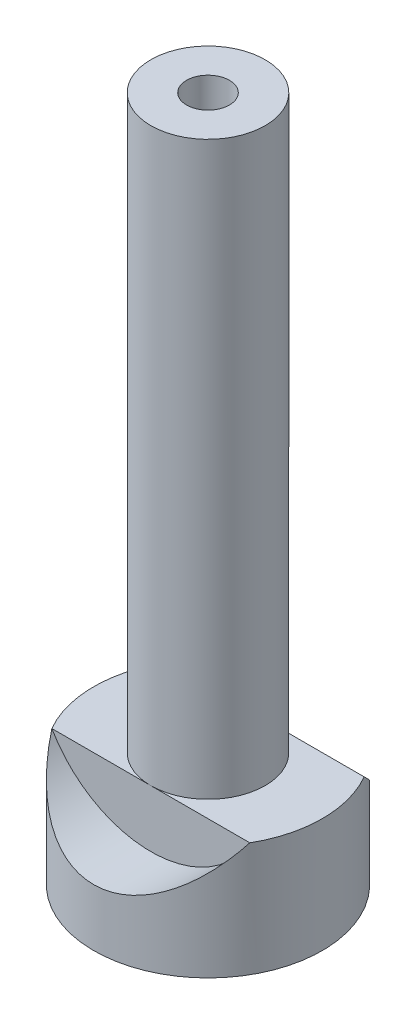
SolidWorks part; units mm, degrees
ref_plane "Front Plane" through (0, 0, 0) normal (0, 0, 1) x (1, 0, 0)
ref_plane "Top Plane" through (0, 0, 0) normal (0, 1, 0) x (1, 0, 0)
ref_plane "Right Plane" through (0, 0, 0) normal (1, 0, 0) x (0, 0, -1)
sketch "Sketch1" plane through (0, 0, 0) normal (0, 1, 0) x (1, 0, 0)
  circle A0 centre (0, 0) radius 6.35
  dimension "D1" = 12.7
extrude "Boss-Extrude1" add sketch "Sketch1" along normal blind 63.5
sketch "Sketch5" plane through (0, 0, 0) normal (0, -1, 0) x (1, 0, 0)
  circle A0 centre (0, 0) radius 12.7
  dimension "D1" = 25.4
extrude "Boss-Extrude2" add sketch "Sketch5" along normal blind 12.7
sketch "Sketch7" plane through (0, 0, 0) normal (0, 1, 0) x (1, 0, 0)
  circle A0 centre (0, 0) radius 8.89
  circle A1 centre (0, 0) radius 6.35
  dimension "D1" = 17.78
ref_plane "Plane1" through (0, 0, 6.35) normal (0, 0, 1) x (1, 0, 0)
sketch "Sketch10" plane through (0, 0, 6.35) normal (0, 0, 1) x (1, 0, 0)
  line L1 (12.7, 0) -> (-12.7, 0) construction
  circle A0 centre (0, 6.35) radius 12.7
  dimension "D1" = 25.4
  dimension "D2" = 6.35
extrude "Cut-Extrude5" cut sketch "Sketch10" along normal through all
ref_plane "Plane2" through (0, 0, -6.35) normal (0, 0, -1) x (-1, 0, 0)
sketch "Sketch12" plane through (0, 0, -6.35) normal (0, 0, -1) x (-1, 0, 0)
  line L0 (8.89, 0) -> (-8.89, 0) construction
  circle A0 centre (0, 6.35) radius 12.7
  dimension "D1" = 25.4
  dimension "D2" = 6.35
extrude "Cut-Extrude6" cut sketch "Sketch12" along normal through all
sketch "Sketch13" plane through (0, 63.5, 0) normal (0, 1, 0) x (1, 0, 0)
  circle A0 centre (0, 0) radius 2.3813
  dimension "D1" = 4.7625
extrude "Cut-Extrude7" cut sketch "Sketch13" against normal blind 50.8
